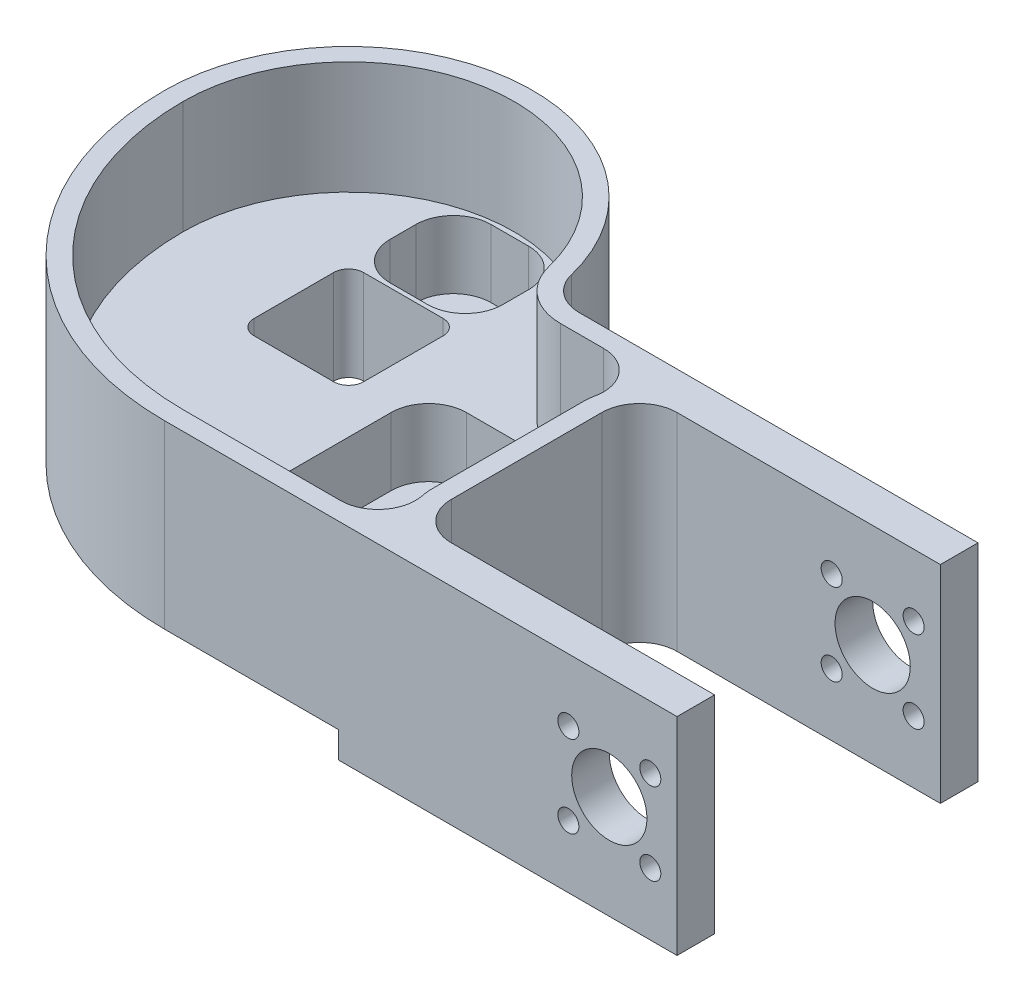
SolidWorks part; units mm, degrees
material "6061-T6 (SS)"
ref_plane "Front Plane" through (0, 0, 0) normal (0, 0, 1) x (1, 0, 0)
ref_plane "Top Plane" through (0, 0, 0) normal (0, 1, 0) x (1, 0, 0)
ref_plane "Right Plane" through (0, 0, 0) normal (1, 0, 0) x (0, 0, -1)
sketch "Sketch1" plane through (0, 0, 0) normal (0, 1, 0) x (1, 0, 0)
  circle A0 centre (0, 0) radius 31.0896
  dimension "D1" = 62.1792
extrude "Boss-Extrude1" add sketch "Sketch1" along normal blind 34.925
sketch "Sketch2" plane through (0, 34.925, 0) normal (0, 1, 0) x (1, 0, 0)
  line L0 (0, 0) -> (-31.0896, 0) construction
  line L1 (0, 0) -> (30.9857, 2.54) construction
  line L2 (46.5427, -48.26) -> (17.1704, -48.26)
  line L4 (46.5427, -48.26) -> (46.5427, 2.54)
  line L7 (30.9857, 2.54) -> (46.5427, 2.54)
  circle A0 centre (0, 0) radius 31.0896 construction
  arc A1 (17.1704, -48.26) -> (-31.0896, 0) centre (17.1704, 0) cw
  circle A2 centre (0, 0) radius 31.0896
  arc A3 (-31.0896, 0) -> (30.9857, 2.54) centre (0, 0) ccw
  dimension "D3" = 2.54
  dimension "D1" = 50.8
  dimension "D2" = 15.557
  dimension "D4" = 0
extrude "Boss-Extrude2" add sketch "Sketch2" against normal blind 30.48
sketch "Sketch3" plane through (0, 34.925, 0) normal (0, 1, 0) x (1, 0, 0)
  line L0 (46.5427, -0.3336) -> (46.5427, -48.26)
  line L1 (17.1704, -48.26) -> (46.5427, -48.26) construction
  line L2 (46.5427, -48.26) -> (103.6927, -48.26)
  line L3 (103.6927, -48.26) -> (103.6927, -41.91)
  line L4 (103.6927, -41.91) -> (52.8927, -41.91)
  line L5 (52.8927, -41.91) -> (52.8927, -3.81)
  line L6 (52.8927, -3.81) -> (103.6927, -3.81)
  line L7 (103.6927, -3.81) -> (103.6927, 2.54)
  line L8 (103.6927, 2.54) -> (46.5427, 2.54)
  line L9 (46.5427, -0.3336) -> (46.5427, 2.54)
  line L10 (46.5427, -48.26) -> (46.5427, 2.54) construction
  dimension "D1" = 57.15
  dimension "D2" = 38.1
  dimension "D3" = 6.35
  dimension "D4" = 6.35
extrude "Boss-Extrude3" add sketch "Sketch3" against normal up to surface (34.925 mm away) up to face at (0, 0, 31.0896)
sketch "Sketch4" plane through (0, 0, -2.54) normal (0, 0, -1) x (-1, 0, 0)
  line L0 (-103.6927, 17.4625) -> (-92.2627, 17.4625) construction
  line L1 (-103.6927, 0) -> (-103.6927, 34.925) construction
  line L2 (-92.2627, 17.4625) -> (-99.1775, 10.5477) construction
  line L3 (-92.2627, 17.4625) -> (-99.1775, 24.3773) construction
  line L4 (-92.2627, 17.4625) -> (-99.1775, 10.5477) construction
  line L5 (-92.2627, 17.4625) -> (-85.3479, 10.5477) construction
  line L6 (-92.2627, 17.4625) -> (-85.3479, 24.3773) construction
  line L8 (-99.1775, 24.3773) -> (-103.6927, 24.3773) construction
  line L9 (-103.6927, 0) -> (-103.6927, 34.925) construction
  line L10 (-99.1775, 10.5477) -> (-103.6927, 10.5477) construction
  circle A0 centre (-92.2627, 17.4625) radius 6.35
  circle A1 centre (-85.3479, 10.5477) radius 1.778
  circle A3 centre (-99.1775, 24.3773) radius 1.778
  circle A4 centre (-99.1775, 10.5477) radius 1.778
  circle A5 centre (-85.3479, 24.3773) radius 1.778
  dimension "D1" = 11.43
  dimension "D2" = 12.7
  dimension "D3" = 3.556
  dimension "D5" = 19.558
  dimension "D4" = 19.558
extrude "Cut-Extrude1" cut sketch "Sketch4" against normal up to surface (50.8 mm away) up to face at (53.3542, 12.7529, 48.26)
sketch "Sketch5" plane through (0, 34.925, 0) normal (0, 1, 0) x (1, 0, 0)
  line L1 (-9.2497, 9.2497) -> (9.2497, 9.2497)
  line L2 (-9.2497, 9.2497) -> (-9.2497, -9.2497)
  line L3 (-9.2497, -9.2497) -> (9.2497, -9.2497)
  line L4 (9.2497, 9.2497) -> (9.2497, -9.2497)
  line L5 (-9.2497, 9.2497) -> (9.2497, -9.2497) construction
  line L6 (-9.2497, -9.2497) -> (9.2497, 9.2497) construction
  point P0 (0, 0)
  dimension "D1" = 26.162
extrude "Cut-Extrude2" cut sketch "Sketch5" against normal up to surface (34.925 mm away) up to face at (0, 0, 31.0896)
fillet "Fillet3" radius 2.54 1 edges at (-9.2497, 17.4625, 9.2497)
fillet "Fillet4" radius 2.54 1 edges at (-9.2497, 17.4625, -9.2497)
fillet "Fillet5" radius 2.54 1 edges at (9.2497, 17.4625, -9.2497)
fillet "Fillet6" radius 2.54 1 edges at (9.2497, 17.4625, 9.2497)
fillet "Fillet8" radius 6.35 1 edges at (30.9857, 19.685, -2.54)
fillet "Fillet9" radius 6.35 1 edges at (52.8927, 17.4625, 41.91)
fillet "Fillet10" radius 6.35 1 edges at (52.8927, 17.4625, 3.81)
sketch "Sketch6" plane through (0, 34.925, 0) normal (0, 1, 0) x (1, 0, 0)
  line L7 (103.6927, 2.54) -> (36.3688, 2.54)
  line L8 (17.1704, -48.26) -> (103.6927, -48.26)
  line L9 (103.6927, -48.26) -> (103.6927, -41.91)
  line L10 (103.6927, -41.91) -> (59.2427, -41.91)
  line L11 (52.8927, -35.56) -> (52.8927, -10.16)
  line L12 (59.2427, -3.81) -> (103.6927, -3.81)
  line L13 (103.6927, -3.81) -> (103.6927, 2.54)
  line L14 (103.6927, 2.54) -> (36.3688, 2.54)
  line L15 (17.1704, -48.26) -> (103.6927, -48.26)
  line L16 (103.6927, -48.26) -> (103.6927, -41.91)
  line L17 (103.6927, -41.91) -> (59.2427, -41.91)
  line L18 (52.8927, -35.56) -> (52.8927, -10.16)
  line L19 (59.2427, -3.81) -> (103.6927, -3.81)
  line L20 (103.6927, -3.81) -> (103.6927, 2.54)
  line L35 (59.2427, -0.635) -> (36.3688, -0.635)
  line L36 (17.1704, -45.085) -> (59.2427, -45.085)
  line L37 (49.7177, -35.56) -> (49.7177, -10.16)
  line L38 (43.6884, -0.635) -> (36.3688, -0.635)
  line L39 (17.1704, -45.085) -> (43.6884, -45.085)
  line L40 (49.7177, -35.56) -> (49.7177, -10.16)
  arc A5 (30.2004, 7.3822) -> (36.3688, 2.54) centre (36.3688, 8.89) ccw
  arc A6 (30.2004, 7.3822) -> (-31.0896, 0) centre (0, 0) ccw
  arc A7 (-31.0896, 0) -> (17.1704, -48.26) centre (17.1704, 0) ccw
  arc A8 (52.8927, -35.56) -> (59.2427, -41.91) centre (59.2427, -35.56) ccw
  arc A9 (59.2427, -3.81) -> (52.8927, -10.16) centre (59.2427, -10.16) ccw
  arc A10 (30.2004, 7.3822) -> (36.3688, 2.54) centre (36.3688, 8.89) ccw
  arc A11 (30.2004, 7.3822) -> (-31.0896, 0) centre (0, 0) ccw
  arc A12 (-31.0896, 0) -> (17.1704, -48.26) centre (17.1704, 0) ccw
  arc A13 (52.8927, -35.56) -> (59.2427, -41.91) centre (59.2427, -35.56) ccw
  arc A14 (59.2427, -3.81) -> (52.8927, -10.16) centre (59.2427, -10.16) ccw
  arc A20 (43.6884, -0.635) -> (49.9101, -8.255) centre (43.6884, -6.985) cw
  arc A21 (43.6884, -45.085) -> (49.9101, -37.465) centre (43.6884, -38.735) ccw
  arc A25 (27.1162, 6.6283) -> (36.3688, -0.635) centre (36.3688, 8.89) ccw
  arc A26 (27.1162, 6.6283) -> (-27.9146, 0) centre (0, 0) ccw
  arc A27 (-27.9146, 0) -> (17.1704, -45.085) centre (17.1704, 0) ccw
  arc A28 (49.7177, -35.56) -> (59.2427, -45.085) centre (59.2427, -35.56) ccw
  arc A29 (59.2427, -0.635) -> (49.7177, -10.16) centre (59.2427, -10.16) ccw
  arc A30 (27.1162, 6.6283) -> (36.3688, -0.635) centre (36.3688, 8.89) ccw
  arc A31 (27.1162, 6.6283) -> (-27.9146, 0) centre (0, 0) ccw
  arc A32 (-27.9146, 0) -> (17.1704, -45.085) centre (17.1704, 0) ccw
  arc A33 (49.7177, -35.56) -> (49.9101, -37.465) centre (59.2427, -35.56) ccw
  arc A34 (49.9101, -8.255) -> (49.7177, -10.16) centre (59.2427, -10.16) ccw
  line M21 (9.2497, 6.7097) -> (9.2497, -6.7097)
  arc M22 (9.2497, -6.7097) -> (6.7097, -9.2497) centre (6.7097, -6.7097) cw
  line M23 (6.7097, -9.2497) -> (-6.7097, -9.2497)
  arc M24 (-6.7097, -9.2497) -> (-9.2497, -6.7097) centre (-6.7097, -6.7097) cw
  line M25 (-9.2497, -6.7097) -> (-9.2497, 6.7097)
  arc M26 (-9.2497, 6.7097) -> (-6.7097, 9.2497) centre (-6.7097, 6.7097) cw
  line M27 (-6.7097, 9.2497) -> (6.7097, 9.2497)
  arc M28 (6.7097, 9.2497) -> (9.2497, 6.7097) centre (6.7097, 6.7097) cw
  dimension "D3" = 6.35
  dimension "D1" = 0
  dimension "D2" = 3.175
extrude "Cut-Extrude3" cut sketch "Sketch6" against normal blind 19.05 contours A34 A20 L38 A30 A31 A32 L39 A21 A33 L40 M28 M21 M22 M23 M24 M25 M26 M27
sketch "Sketch8" plane through (0, 15.875, 0) normal (0, 1, 0) x (1, 0, 0)
  line L1 (22.4127, -2.54) -> (41.4627, -2.54)
  line L2 (16.0627, -8.89) -> (16.0627, -36.83)
  line L3 (47.8127, -8.89) -> (47.8127, -36.83)
  line L6 (22.4127, -43.18) -> (41.4627, -43.18)
  line L7 (103.6927, 2.54) -> (36.3688, 2.54) construction
  line L8 (52.8927, -35.56) -> (52.8927, -10.16) construction
  line L9 (17.1704, -48.26) -> (103.6927, -48.26) construction
  arc A0 (16.0627, -36.83) -> (22.4127, -43.18) centre (22.4127, -36.83) ccw
  arc A1 (47.8127, -36.83) -> (41.4627, -43.18) centre (41.4627, -36.83) cw
  arc A2 (41.4627, -2.54) -> (47.8127, -8.89) centre (41.4627, -8.89) cw
  arc A3 (16.0627, -8.89) -> (22.4127, -2.54) centre (22.4127, -8.89) cw
  dimension "D1" = 6.35
  dimension "D2" = 5.08
  dimension "D3" = 5.08
  dimension "D4" = 31.75
  dimension "D5" = 5.08
extrude "Cut-Extrude4" cut sketch "Sketch8" against normal up to surface (11.43 mm away) up to face at (21.5778, 4.445, 25.8461)
sketch "Sketch9" plane through (0, 15.875, 0) normal (0, 1, 0) x (1, 0, 0)
  line L0 (-9.3373, 20.6797) -> (-9.3373, 16.3202)
  line L1 (-2.9873, 9.9702) -> (3.3627, 9.9702)
  line L2 (9.7127, 16.3202) -> (9.7127, 20.6797)
  line L3 (-2.9873, 27.0297) -> (3.3627, 27.0297)
  line L4 (-6.7097, 9.2497) -> (6.7097, 9.2497) construction
  line L5 (16.0627, -26.6187) -> (16.0627, -8.89) construction
  line L6 (-9.2497, -6.7097) -> (-9.2497, 6.7097) construction
  line L7 (9.2497, 6.7097) -> (9.2497, -6.7097) construction
  arc A0 (3.3627, 9.9702) -> (9.7127, 16.3202) centre (3.3627, 16.3202) ccw
  arc A1 (-9.3373, 16.3202) -> (-2.9873, 9.9702) centre (-2.9873, 16.3202) ccw
  arc A2 (-9.3373, 20.6797) -> (-2.9873, 27.0297) centre (-2.9873, 20.6797) cw
  arc A3 (9.7127, 20.6797) -> (3.3627, 27.0297) centre (3.3627, 20.6797) ccw
  dimension "D1" = 6.35
  dimension "D2" = 0.7205
  dimension "D3" = 17.78
  dimension "D4" = 19.05
  dimension "D5" = 6.35
extrude "Cut-Extrude5" cut sketch "Sketch9" against normal up to surface (11.43 mm away) up to face at (17.7125, 4.445, 39.5566)
